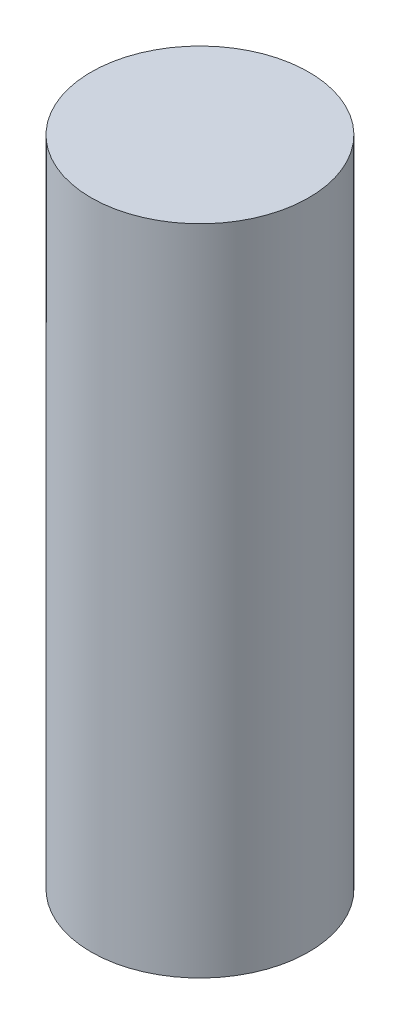
SolidWorks part; units mm, degrees
ref_plane "Front Plane" through (0, 0, 0) normal (0, 0, 1) x (1, 0, 0)
ref_plane "Top Plane" through (0, 0, 0) normal (0, 1, 0) x (1, 0, 0)
ref_plane "Right Plane" through (0, 0, 0) normal (1, 0, 0) x (0, 0, -1)
sketch "Sketch1" plane through (0, 0, 0) normal (0, 1, 0) x (1, 0, 0)
  circle A0 centre (0, 0) radius 50
extrude "Boss-Extrude1" add sketch "Sketch1" along normal blind 300
